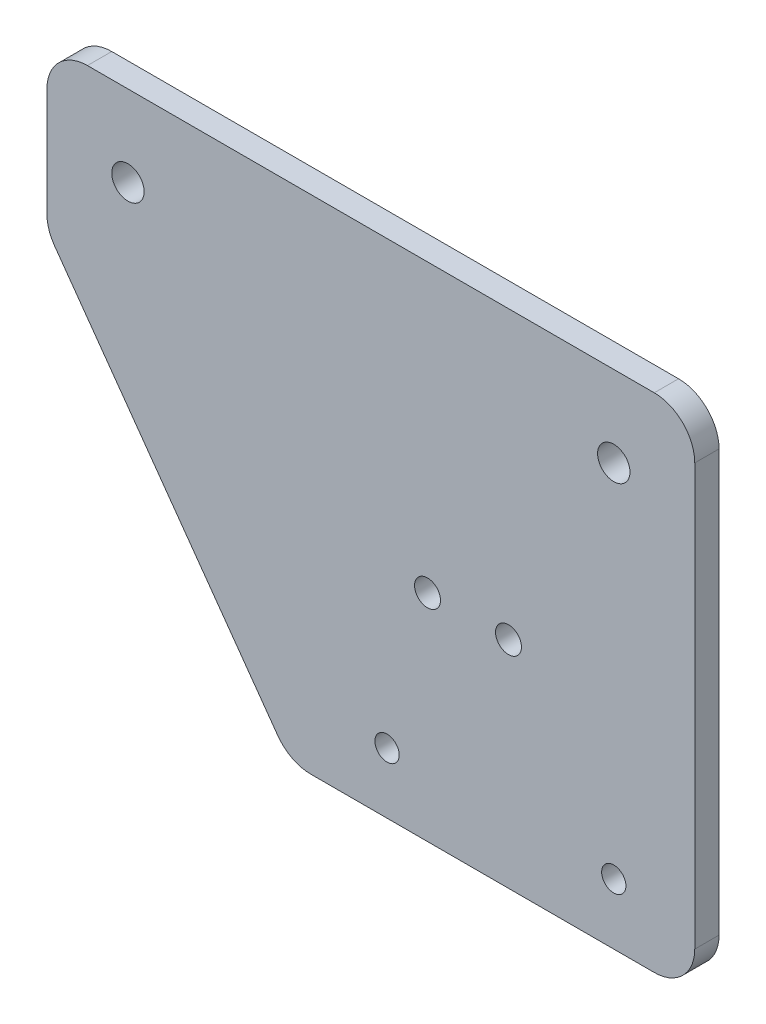
SolidWorks part; units mm, degrees
ref_plane "前视基准面" through (0, 0, 0) normal (0, 0, 1) x (1, 0, 0)
ref_plane "上视基准面" through (0, 0, 0) normal (0, 1, 0) x (1, 0, 0)
ref_plane "右视基准面" through (0, 0, 0) normal (1, 0, 0) x (0, 0, -1)
sketch "草图1" plane through (0, 0, 0) normal (0, 0, 1) x (1, 0, 0)
  line L1 (-42.5, 31) -> (37.5, 31)
  line L2 (-42.5, 31) -> (-42.5, -31)
  line L3 (-42.5, -31) -> (37.5, -31)
  line L4 (37.5, 31) -> (37.5, -31)
  line L5 (-42.5, 31) -> (37.5, -31) construction
  line L6 (-42.5, -31) -> (37.5, 31) construction
  point P0 (0, 0)
extrude "凸台-拉伸1" add sketch "草图1" along normal blind 3
hole_wizard "Ø4.0 (4) 直径孔1" positions "草图3" profile "草图2" hole size "Ø4.0" standard "GB" end condition through all
sketch "草图3" plane through (0, 0, 3) normal (0, 0, 1) x (1, 0, 0)
  line L0 (37.5, 21) -> (27.5, 21)
  line L1 (37.5, -31) -> (37.5, 31) construction
  line L2 (27.5, 21) -> (27.5, 31)
  line L3 (37.5, 31) -> (-42.5, 31) construction
  line L4 (-42.5, 21) -> (-32.5, 21)
  line L5 (-42.5, 31) -> (-42.5, -31) construction
  point P0 (27.5, 21)
  point P15 (-32.5, 21)
sketch "草图2" plane through (27.5, 21, 3) normal (1, 0, 0) x (0, -1, 0)
  line L0 (0, 0) -> (0, 3)
  line L1 (0, 3) -> (2, 3)
  line L2 (2, 3) -> (2, 0)
  line L5 (2, 0) -> (0, 0)
  line L11 (0, -6.35) -> (0, 107.95) construction
  dimension "通孔孔直径" = 4
  dimension "通孔孔深度" = 3
hole_wizard "Ø3.2 (3.2) 直径孔1" positions "草图5" profile "草图4" hole size "Ø3.2" standard "GB" end condition through all
sketch "草图5" plane through (0, 0, 3) normal (0, 0, 1) x (1, 0, 0)
  line L0 (14.5, 31) -> (14.5, -4.4)
  line L1 (37.5, 31) -> (-42.5, 31) construction
  line L2 (14.5, -4.4) -> (37.5, -4.4)
  line L3 (37.5, -31) -> (37.5, 31) construction
  line L4 (14.5, -4.4) -> (4.5, -4.4)
  point P2 (14.5, -4.4)
  point P14 (4.5, -4.4)
sketch "草图4" plane through (14.5, -4.4, 3) normal (1, 0, 0) x (0, -1, 0)
  line L0 (0, 0) -> (0, 3)
  line L1 (0, 3) -> (1.6, 3)
  line L2 (1.6, 3) -> (1.6, 0)
  line L5 (1.6, 0) -> (0, 0)
  line L11 (0, -6.35) -> (0, 107.95) construction
  dimension "通孔孔直径" = 3.2
  dimension "通孔孔深度" = 3
sketch "草图6" plane through (0, 0, 3) normal (0, 0, 1) x (1, 0, 0)
  line L0 (-42.5, 11) -> (-42.5, -31)
  line L1 (-542.5, 11) -> (-337.5, 11) construction
  line L2 (-42.5, 31) -> (-42.5, -31) construction
  line L3 (-42.5, -31) -> (-12.5, -31)
  line L4 (-42.5, -31) -> (37.5, -31) construction
  line L5 (-12.5, -31) -> (-42.5, 11)
extrude "切除-拉伸1" cut sketch "草图6" against normal blind 3
hole_wizard "Ø3.0 (3) 直径孔1" positions "草图8" profile "草图7" hole size "Ø3.0" standard "GB" end condition through all
sketch "草图8" plane through (0, 0, 3) normal (0, 0, 1) x (1, 0, 0)
  line L0 (27.5, -23.5) -> (27.5, -31)
  line L1 (-12.5, -31) -> (37.5, -31) construction
  line L2 (27.5, -31) -> (37.5, -31)
  line L7 (-42.5, 11) -> (-12.5, -31)
  line L10 (-32.5, 21) -> (-44.5458, 13.8641)
  line L20 (27.5, -23.5) -> (-0.5, -23.5)
  point P0 (27.5, -23.5)
  point P77 (-0.5, -23.5)
sketch "草图7" plane through (27.5, -23.5, 3) normal (1, 0, 0) x (0, -1, 0)
  line L0 (0, 0) -> (0, 3)
  line L1 (0, 3) -> (1.5, 3)
  line L2 (1.5, 3) -> (1.5, 0)
  line L5 (1.5, 0) -> (0, 0)
  line L11 (0, -6.35) -> (0, 107.95) construction
  dimension "通孔孔直径" = 3
  dimension "通孔孔深度" = 3
fillet "圆角1" radius 5 5 edges at (-42.5, 31, 1.5) (-42.5, 11, 1.5) (37.5, 31, 1.5) (37.5, -31, 1.5) (-12.5, -31, 1.5)
